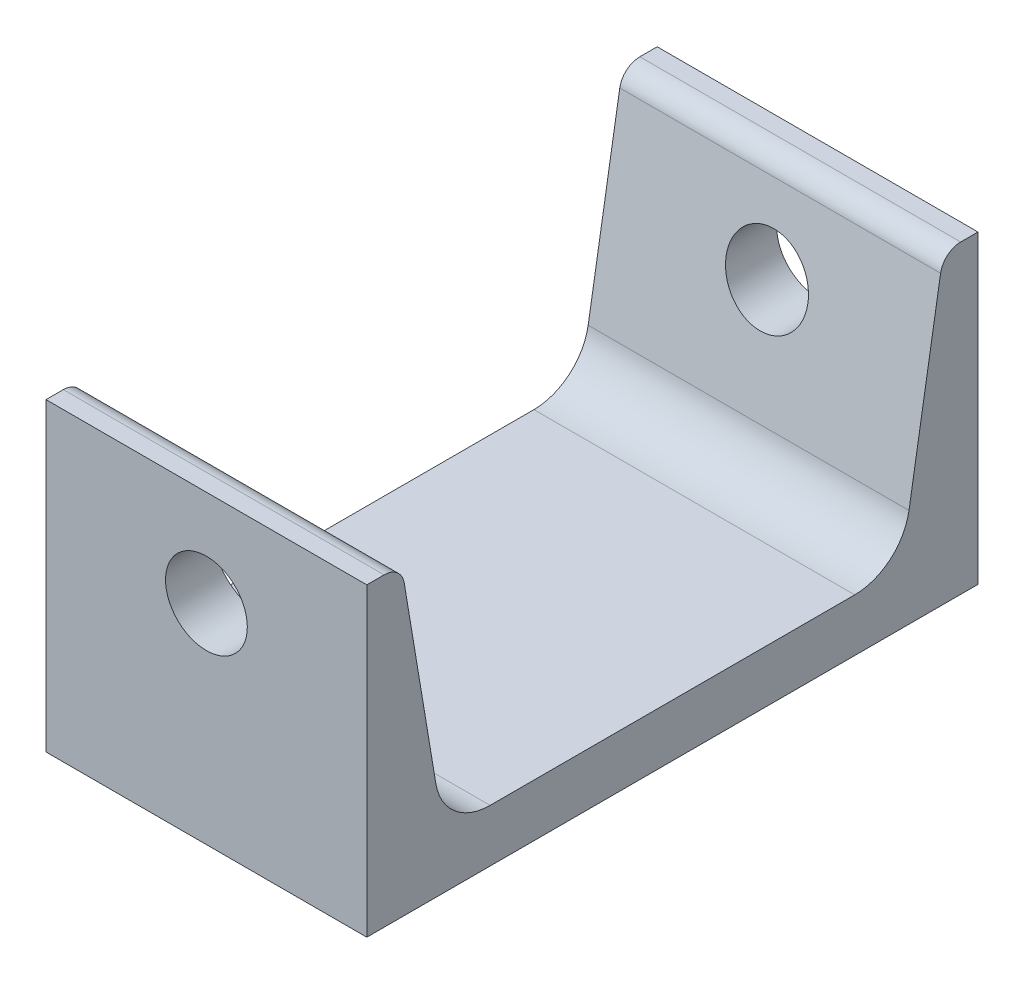
SolidWorks part; units mm, degrees
other "Carpeta de soldadura"
material "AISI 1010 Barra de acero laminada en caliente"
ref_plane "Alzado" through (0, 0, 0) normal (0, 0, 1) x (1, 0, 0)
ref_plane "Planta" through (0, 0, 0) normal (0, 1, 0) x (1, 0, 0)
ref_plane "Vista lateral" through (0, 0, 0) normal (1, 0, 0) x (0, 0, -1)
sketch "Croquis1" plane through (0, 0, 0) normal (0, 0, 1) x (1, 0, 0)
  line L0 (-18.5367, 0) -> (21.4633, 0)
  dimension "D1" = 40
other "Miembro estructural1"
ref_plane "Plano1" through (-18.5367, 0, 0) normal (1, 0, 0) x (0, 1, 0)
sketch "Sketch1" plane through (-18.5367, 0, 0) normal (1, 0, 0) x (0, 1, 0)
  line L0 (0, -38.1) -> (0, 38.1)
  line L1 (0, 38.1) -> (38.0492, 38.1)
  line L2 (0, -38.1) -> (38.0492, -38.1)
  line L5 (31.75, -31.1658) -> (6.35, -31.1658) construction
  line L6 (0, 0) -> (6.5532, 0) construction
  line L12 (6.5532, 22.7314) -> (6.5532, -22.7314)
  line L15 (38.0492, 38.1) -> (38.0492, 35.9423)
  line L16 (38.0492, -38.1) -> (38.0492, -35.9423)
  line L17 (12.2837, 29.4961) -> (35.9268, 33.4369)
  line L18 (12.2837, -29.4961) -> (35.9268, -33.4369)
  arc A9 (6.5532, -22.7314) -> (12.2837, -29.4961) centre (13.4112, -22.7314) ccw
  arc A10 (6.5532, 22.7314) -> (12.2837, 29.4961) centre (13.4112, 22.7314) cw
  arc A11 (38.0492, 35.9423) -> (35.9268, 33.4369) centre (35.5092, 35.9423) cw
  arc A12 (38.0492, -35.9423) -> (35.9268, -33.4369) centre (35.5092, -35.9423) ccw
  point P4 (38.0492, 33.7907)
  point P5 (38.0492, -33.7907)
  point P6 (3.2766, 0)
  point P7 (19.0246, 38.1)
  point P12 (19.0246, -38.1)
  point P13 (0, 0)
  dimension "RI" = 6.858
  dimension "D2" = 9.463
  dimension "RA" = 2.54
  dimension "Depth" = 76.2
  dimension "BF" = 38.0492
  dimension "TW" = 6.5532
  dimension "flange" = 2.1577
  dimension "TF" = 6.9342
sketch "Croquis19" plane through (0, 0, 38.1) normal (0, 0, 1) x (1, 0, 0)
  line L0 (21.4633, 38.0492) -> (21.4633, 0) construction
  line L1 (-18.5367, 0) -> (21.4633, 0)
  line L2 (-18.5367, 0) -> (-18.5367, 60)
  line L3 (-18.5367, 60) -> (21.4633, 60)
  line L4 (21.4633, 0) -> (21.4633, 60)
  dimension "D1" = 60
sketch "Croquis20" plane through (0, 0, -38.1) normal (0, 0, -1) x (-1, 0, 0)
  line L0 (18.5367, 0) -> (18.5367, 38.0492) construction
  line L1 (-21.4633, 0) -> (18.5367, 0)
  line L2 (-21.4633, 0) -> (-21.4633, 60)
  line L3 (-21.4633, 60) -> (18.5367, 60)
  line L4 (18.5367, 0) -> (18.5367, 60)
  dimension "D1" = 60
sketch "Croquis4" plane through (0, 0, 38.1) normal (0, 0, 1) x (1, 0, 0)
  line L2 (1.4633, 38.0492) -> (1.4633, 9.9981) construction
  line L6 (21.4633, 38.0492) -> (-18.5367, 38.0492) construction
  line L7 (21.4633, 38.0492) -> (-18.5367, 38.0492) construction
  circle A0 centre (1.4633, 26.0492) radius 5.1
  dimension "D1" = 10.2
  dimension "D2" = 12
ref_plane "Plano2" through (1.4633, 0, 0) normal (1, 0, 0) x (0, 0, -1)
extrude "Cortar-Extruir1" cut sketch "Croquis4" against normal through all contours A0
sketch "Líneas de pliegue3" [suppressed] plane through (0, 0, 0) normal (0, 1, 0) x (1, 0, 0)
sketch "Cuadro delimitador3" [suppressed] plane through (0, 0, 0) normal (0, 1, 0) x (1, 0, 0)
